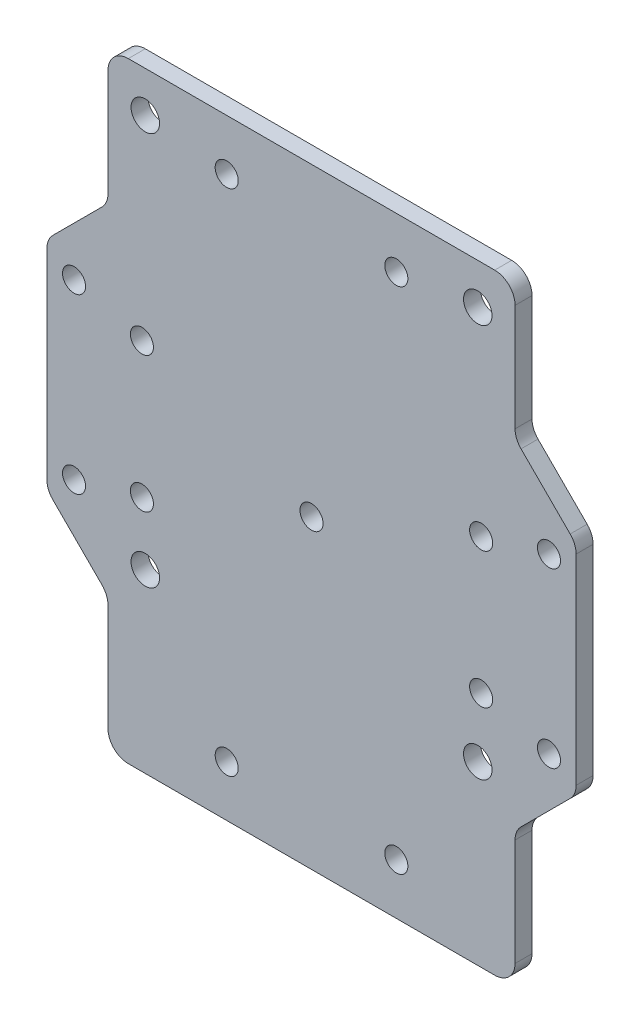
SolidWorks part; units mm, degrees
material "Thornel Mat VMA"
ref_plane "Front Plane" through (0, 0, 0) normal (0, 0, 1) x (1, 0, 0)
ref_plane "Top Plane" through (0, 0, 0) normal (0, 1, 0) x (1, 0, 0)
ref_plane "Right Plane" through (0, 0, 0) normal (1, 0, 0) x (0, 0, -1)
sketch "Sketch1" plane through (0, 0, 0) normal (0, 0, 1) x (1, 0, 0)
  line L0 (-39, -16) -> (-39, 16)
  line L5 (-30, 45) -> (30, 45)
  line L6 (-30, 45) -> (-30, -45)
  line L12 (-30, -45) -> (30, -45)
  line L17 (30, 45) -> (30, -45)
  line L19 (-30, 45) -> (30, -45) construction
  line L20 (-30, -45) -> (30, 45) construction
  line L21 (-39, 0) -> (39, 0) construction
  line L22 (-39, 16) -> (-30, 25)
  line L23 (-39, -16) -> (-30, -25)
  line L24 (0, 0) -> (0, 25) construction
  line L25 (39, -16) -> (30, -25)
  line L26 (39, 16) -> (30, 25)
  line L27 (39, -16) -> (39, 16)
  point P0 (0, 0)
  dimension "D1" = 60
  dimension "D2" = 90
  dimension "D3" = 9
  dimension "D4" = 16
  dimension "D5" = 135
extrude "Boss-Extrude1" add sketch "Sketch1" along normal mid plane 2.5
fillet "Fillet1" radius 3 12 edges at (30, 45, 0) (30, -45, 0) (-30, -45, 0) (-30, 45, 0) (30, 25, 0) (39, 16, 0) (39, -16, 0) (30, -25, 0) (-30, -25, 0) (-39, -16, 0) (-39, 16, 0) (-30, 25, 0)
hole_wizard "Ø4.2 (4.2) Diameter Hole1" positions "Sketch2" profile "Sketch3" hole size "Ø4.2" standard "ANSI Metric" end condition through all
sketch "Sketch2" plane through (0, 0, -1.25) normal (0, 0, -1) x (-1, 0, 0)
  point P0 (-24.5, -19)
  point P3 (24.5, -19)
  point P6 (24.5, 39)
  point P9 (-24.5, 39)
sketch "Sketch3" plane through (24.5, -19, -1.25) normal (1, 0, 0) x (0, 1, 0)
  line L0 (0, 0) -> (0, 2.5)
  line L1 (0, 2.5) -> (2.1, 2.5)
  line L2 (2.1, 2.5) -> (2.1, 0)
  line L5 (2.1, 0) -> (0, 0)
  line L11 (0, -6.35) -> (0, 107.95) construction
  dimension "Thru Hole Dia." = 4.2
  dimension "Thru Hole Depth" = 2.5
hole_wizard "M3 Clearance Hole1" positions "Sketch4" profile "Sketch5" hole size "M3" standard "ANSI Metric" end condition through all
sketch "Sketch4" plane through (0, 0, -1.25) normal (0, 0, -1) x (-1, 0, 0)
  point P0 (-35, 12.75)
  point P3 (-35, -12.75)
  point P6 (35, -12.75)
  point P9 (35, 12.75)
sketch "Sketch5" plane through (35, 12.75, -1.25) normal (1, 0, 0) x (0, 1, 0)
  line L0 (0, 0) -> (0, 2.5)
  line L1 (0, 2.5) -> (1.7, 2.5)
  line L2 (1.7, 2.5) -> (1.7, 0)
  line L5 (1.7, 0) -> (0, 0)
  line L11 (0, -6.35) -> (0, 107.95) construction
  dimension "Thru Hole Dia." = 3.4
  dimension "Thru Hole Depth" = 2.5
hole_wizard "M3 Clearance Hole2" positions "Sketch6" profile "Sketch7" hole size "M3" standard "ANSI Metric" end condition through all
sketch "Sketch6" plane through (0, 0, 1.25) normal (0, 0, 1) x (1, 0, 0)
  point P0 (-12.5, -37.5)
  point P3 (12.5, -37.5)
  point P6 (-12.5, 37.5)
  point P9 (12.5, 37.5)
  point P12 (-25, 10)
  point P15 (-25, -10)
  point P18 (25, -10)
  point P21 (25, 10)
sketch "Sketch7" plane through (-12.5, -37.5, 1.25) normal (1, 0, 0) x (0, -1, 0)
  line L0 (0, 0) -> (0, 2.5)
  line L1 (0, 2.5) -> (1.7, 2.5)
  line L2 (1.7, 2.5) -> (1.7, 0)
  line L5 (1.7, 0) -> (0, 0)
  line L11 (0, -6.35) -> (0, 107.95) construction
  dimension "Thru Hole Dia." = 3.4
  dimension "Thru Hole Depth" = 2.5
hole_wizard "M3 Clearance Hole3" positions "Sketch8" profile "Sketch9" hole size "M3" standard "ANSI Metric" end condition through all
sketch "Sketch8" plane through (0, 0, 1.25) normal (0, 0, 1) x (1, 0, 0)
  point P0 (0, 0)
sketch "Sketch9" plane through (0, 0, 1.25) normal (1, 0, 0) x (0, -1, 0)
  line L0 (0, 0) -> (0, 2.5)
  line L1 (0, 2.5) -> (1.7, 2.5)
  line L2 (1.7, 2.5) -> (1.7, 0)
  line L5 (1.7, 0) -> (0, 0)
  line L11 (0, -6.35) -> (0, 107.95) construction
  dimension "Thru Hole Dia." = 3.4
  dimension "Thru Hole Depth" = 2.5
